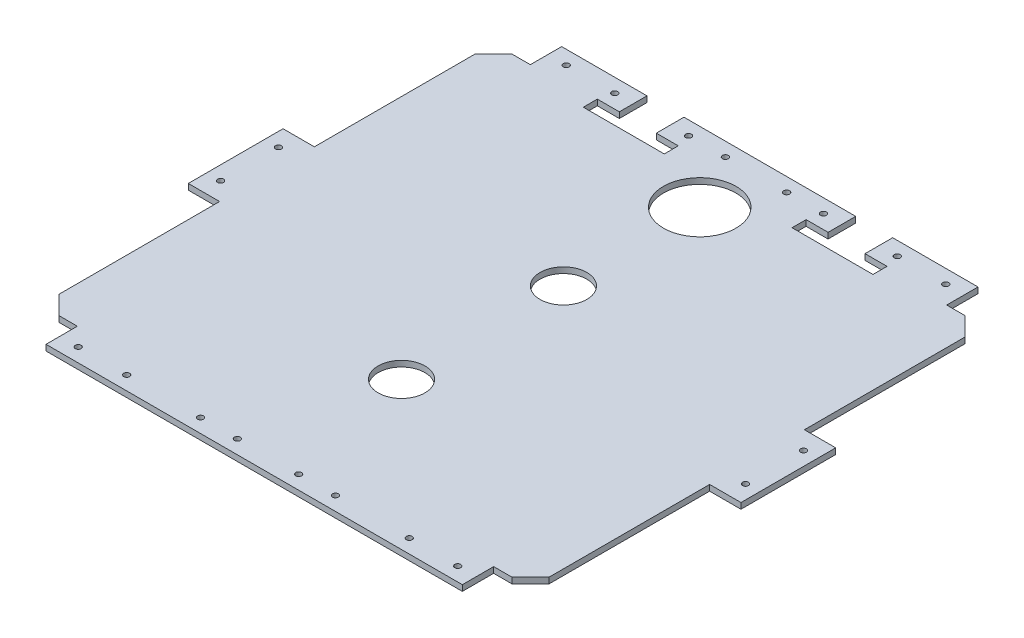
SolidWorks part; units mm, degrees
ref_plane "Front Plane" through (0, 0, 0) normal (0, 0, 1) x (1, 0, 0)
ref_plane "Top Plane" through (0, 0, 0) normal (0, 1, 0) x (1, 0, 0)
ref_plane "Right Plane" through (0, 0, 0) normal (1, 0, 0) x (0, 0, -1)
sketch "Sketch1" plane through (0, 0, 0) normal (0, 1, 0) x (1, 0, 0)
  line L1 (0, 0) -> (300, 0)
  line L2 (0, 0) -> (0, 279.908)
  line L3 (0, 279.908) -> (300, 279.908)
  line L4 (300, 0) -> (300, 279.908)
  dimension "D1" = 300
  dimension "D2" = 279.908
extrude "Boss-Extrude1" add sketch "Sketch1" along normal blind 3.175
sketch "Sketch2" plane through (0, 3.175, 0) normal (0, 1, 0) x (1, 0, 0)
  line L0 (263, 17) -> (273, 17)
  line L1 (300, 0) -> (283, 0)
  line L2 (300, 0) -> (300, 114.24)
  line L3 (300, 114.24) -> (283, 114.24)
  line L4 (283, 0) -> (283, 114.24)
  line L9 (300, 0) -> (263, 0)
  line L10 (300, 0) -> (300, 17)
  line L11 (300, 17) -> (263, 17)
  line L12 (263, 0) -> (263, 17)
  line L13 (273, 17) -> (283, 27)
  line L14 (150, 0) -> (150, 279.908)
  line L15 (0, 0) -> (300, 0) construction
  line L16 (300, 279.908) -> (0, 279.908) construction
  line L17 (300, 139.954) -> (0, 139.954)
  line L18 (300, 0) -> (300, 279.908) construction
  line L19 (0, 279.908) -> (0, 0) construction
  line L20 (27, 17) -> (17, 27)
  line L21 (37, 0) -> (37, 17)
  line L22 (0, 17) -> (37, 17)
  line L23 (0, 0) -> (0, 17)
  line L24 (0, 0) -> (37, 0)
  line L25 (17, 0) -> (17, 114.24)
  line L26 (0, 114.24) -> (17, 114.24)
  line L27 (0, 0) -> (0, 114.24)
  line L28 (0, 0) -> (17, 0)
  line L29 (37, 17) -> (27, 17)
  line L30 (37, 262.908) -> (27, 262.908)
  line L31 (0, 279.908) -> (17, 279.908)
  line L32 (0, 279.908) -> (0, 165.668)
  line L33 (0, 165.668) -> (17, 165.668)
  line L34 (17, 279.908) -> (17, 165.668)
  line L35 (0, 279.908) -> (37, 279.908)
  line L36 (0, 279.908) -> (0, 262.908)
  line L37 (0, 262.908) -> (37, 262.908)
  line L38 (37, 279.908) -> (37, 262.908)
  line L39 (27, 262.908) -> (17, 252.908)
  line L40 (273, 262.908) -> (283, 252.908)
  line L41 (263, 279.908) -> (263, 262.908)
  line L42 (300, 262.908) -> (263, 262.908)
  line L43 (300, 279.908) -> (300, 262.908)
  line L44 (300, 279.908) -> (263, 279.908)
  line L45 (283, 279.908) -> (283, 165.668)
  line L46 (300, 165.668) -> (283, 165.668)
  line L47 (300, 279.908) -> (300, 165.668)
  line L48 (300, 279.908) -> (283, 279.908)
  line L49 (263, 262.908) -> (273, 262.908)
  line L50 (228.626, 264.908) -> (228.626, 257.288)
  line L51 (83.312, 279.908) -> (103.378, 279.908)
  line L52 (83.312, 279.908) -> (83.312, 264.908)
  line L53 (83.312, 264.908) -> (103.378, 264.908)
  line L54 (103.378, 279.908) -> (103.378, 264.908)
  line L55 (115.316, 264.908) -> (71.374, 264.908)
  line L56 (115.316, 264.908) -> (115.316, 257.288)
  line L57 (115.316, 257.288) -> (71.374, 257.288)
  line L58 (71.374, 264.908) -> (71.374, 257.288)
  line L59 (184.684, 257.288) -> (228.626, 257.288)
  line L60 (184.684, 264.908) -> (184.684, 257.288)
  line L61 (184.684, 264.908) -> (228.626, 264.908)
  line L62 (196.622, 279.908) -> (196.622, 264.908)
  line L63 (216.688, 264.908) -> (196.622, 264.908)
  line L64 (216.688, 279.908) -> (216.688, 264.908)
  line L65 (216.688, 279.908) -> (196.622, 279.908)
  point P60 (93.345, 264.908)
  point P61 (93.345, 264.908)
  point P70 (206.655, 264.908)
  line M20 (0, 279.908) -> (0, 0)
  line M21 (0, 0) -> (300, 0)
  line M22 (300, 0) -> (300, 279.908)
  line M23 (300, 279.908) -> (0, 279.908)
  dimension "D1" = 114.24
  dimension "D2" = 20.066
  dimension "D3" = 17
  dimension "D4" = 83.312
  dimension "D5" = 17
  dimension "D6" = 37
  dimension "D7" = 10
  dimension "D8" = 45
  dimension "D9" = 15
  dimension "D10" = 43.942
  dimension "D11" = 7.62
extrude "Cut-Extrude1" cut sketch "Sketch2" against normal blind 3.175 contours L13 L11 L4 | L12 L4 L11 L0 M21 | L11 L4 M22 M21 | L11 L2 L3 L4 | L45 L42 L40 | L46 L42 L45 M22 | L45 L42 M23 M22 | L45 L44 L41 L42 | L25 L22 L20 | L25 L24 L21 L22 | L25 L22 M21 M20 | L26 L22 L25 M20 | L39 L37 L34 | L38 L34 L37 L30 M23 | L37 L34 M20 M23 | L37 L32 L33 L34 | L54 L52 L53 M23 | L55 L58 L57 L56 L53 | L64 L62 L61 M23 | L61 L60 L59 L50
sketch "Sketch3" plane through (0, 3.175, 0) normal (0, 1, 0) x (1, 0, 0)
  line L0 (263, 279.908) -> (216.688, 279.908) construction
  line L1 (37, 0) -> (263, 0) construction
  line L2 (263, 7.5) -> (37, 7.5)
  line L3 (300, 114.24) -> (300, 165.668) construction
  line L4 (0, 165.668) -> (0, 114.24) construction
  line L5 (300, 165.668) -> (283, 165.668) construction
  line L6 (300, 114.24) -> (285, 114.24)
  line L7 (300, 114.24) -> (300, 165.668)
  line L8 (300, 165.668) -> (285, 165.668)
  line L9 (285, 114.24) -> (285, 165.668)
  line L10 (0, 165.668) -> (17, 165.668) construction
  line L11 (0, 114.24) -> (15, 114.24)
  line L12 (0, 114.24) -> (0, 165.668)
  line L13 (0, 165.668) -> (15, 165.668)
  line L14 (15, 114.24) -> (15, 165.668)
  line L15 (263, 279.908) -> (263, 262.908) construction
  line L16 (37, 279.908) -> (263, 279.908)
  line L17 (37, 279.908) -> (37, 264.908)
  line L18 (37, 264.908) -> (263, 264.908)
  line L19 (263, 279.908) -> (263, 264.908)
  line L20 (37, 0) -> (37, 17) construction
  line L21 (263, 0) -> (37, 0)
  line L22 (263, 0) -> (263, 15)
  line L23 (263, 15) -> (37, 15)
  line L24 (37, 0) -> (37, 15)
  line L25 (292.5, 114.24) -> (292.5, 165.668)
  line L26 (263, 272.408) -> (37, 272.408)
  line L27 (7.5, 114.24) -> (7.5, 165.668)
  line L28 (150, 279.908) -> (150, 0)
  line L29 (0, 139.954) -> (300, 139.954)
  line L30 (83.312, 279.908) -> (83.312, 264.908) construction
  line L31 (103.378, 279.908) -> (103.378, 264.908) construction
  circle A0 centre (150, 241.858) radius 19.685
  circle A1 centre (150, 80) radius 12.7
  circle A2 centre (150, 167.8736) radius 12.7
  circle A3 centre (47, 272.408) radius 1.6
  circle A4 centre (73.312, 272.408) radius 1.6
  circle A5 centre (113.378, 272.408) radius 1.6
  circle A6 centre (133.378, 272.408) radius 1.6
  circle A7 centre (166.622, 272.408) radius 1.6
  circle A8 centre (186.622, 272.408) radius 1.6
  circle A9 centre (226.688, 272.408) radius 1.6
  circle A10 centre (253, 272.408) radius 1.6
  circle A11 centre (253, 7.5) radius 1.6
  circle A12 centre (226.688, 7.5) radius 1.6
  circle A13 centre (186.622, 7.5) radius 1.6
  circle A14 centre (166.622, 7.5) radius 1.6
  circle A15 centre (133.378, 7.5) radius 1.6
  circle A16 centre (113.378, 7.5) radius 1.6
  circle A17 centre (73.312, 7.5) radius 1.6
  circle A18 centre (47, 7.5) radius 1.6
  circle A19 centre (7.5, 155.668) radius 1.6
  circle A20 centre (7.5, 124.24) radius 1.6
  circle A21 centre (292.5, 124.24) radius 1.6
  circle A22 centre (292.5, 155.668) radius 1.6
  dimension "D2" = 39.37
  dimension "D4" = 25.4
  dimension "D7" = 25.4
  dimension "D13" = 3.2
  dimension "D14" = 3.2
  dimension "D1" = 38.05
  dimension "D3" = 80
  dimension "D5" = 150
  dimension "D6" = 150
  dimension "D8" = 150
  dimension "D9" = 15
  dimension "D10" = 15
  dimension "D11" = 15
  dimension "D12" = 15
  dimension "D15" = 10
  dimension "D16" = 10
  dimension "D17" = 10
  dimension "D18" = 10
  dimension "D19" = 20
extrude "Cut-Extrude2" cut sketch "Sketch3" against normal blind 3.175 contours A2 | L28 A2 | A0 | A1 | A19 | A20 | A18 | A17 | A16 | A15 | A14 | A13 | A12 | A11 | A3 | A4 | A5 | A6 | A7 | A8 | A9 | A10 | A22 | A21
